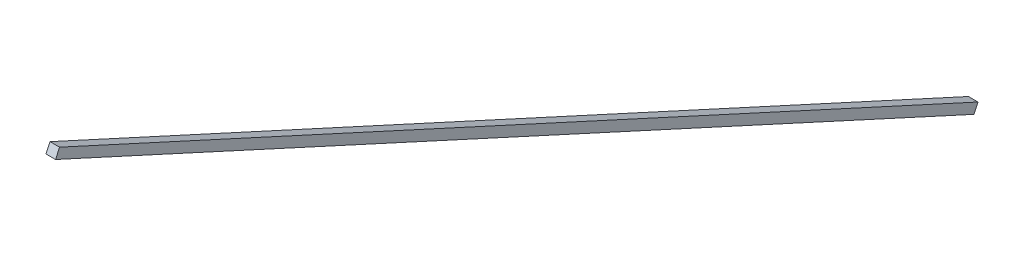
SolidWorks part; units mm, degrees
ref_plane "Front Plane" through (0, 0, 0) normal (0, 0, 1) x (1, 0, 0)
ref_plane "Top Plane" through (0, 0, 0) normal (0, 1, 0) x (1, 0, 0)
ref_plane "Right Plane" through (0, 0, 0) normal (1, 0, 0) x (0, 0, -1)
sketch "Sketch1" plane through (0.0025, -3.7675, -8.2391) normal (-0.0003, 0.4159, 0.9094) x (1, 0.0001, 0.0003)
  line L1 (21.659, -66.9689) -> (23.659, -66.9689)
  line L2 (21.659, -66.9689) -> (21.659, -64.9689)
  line L3 (21.659, -64.9689) -> (23.659, -64.9689)
  line L4 (23.659, -66.9689) -> (23.659, -64.9689)
  line L5 (21.659, -66.9689) -> (23.659, -64.9689) construction
  line L6 (21.659, -64.9689) -> (23.659, -66.9689) construction
  arc A0 (23.0813, -55.9778) -> (25.4964, -56.3799) centre (22.659, -65.9689) ccw construction
  arc A1 (23.0813, -55.9778) -> (25.4964, -56.3799) centre (22.659, -65.9689) ccw construction
  point P0 (22.659, -65.9689)
  dimension "D1" = 2
  dimension "D2" = 2
extrude "Boss-Extrude1" add sketch "Sketch1" along normal blind 211 contours L4 L3 L2 L1
equation "\"D2@Sketch1\"=\"D1@Sketch1\""
